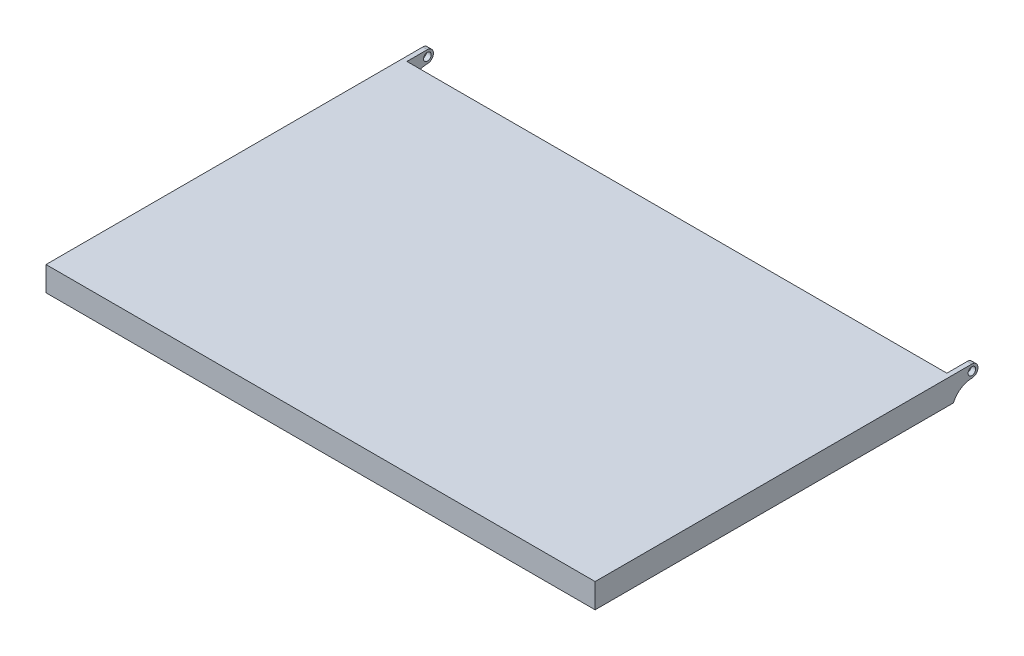
SolidWorks part; units mm, degrees
ref_plane "Alzado" through (0, 0, 0) normal (0, 0, 1) x (1, 0, 0)
ref_plane "Planta" through (0, 0, 0) normal (0, 1, 0) x (1, 0, 0)
ref_plane "Vista lateral" through (0, 0, 0) normal (1, 0, 0) x (0, 0, -1)
sketch "Croquis1" plane through (0, 0, 0) normal (0, 1, 0) x (1, 0, 0)
  line L0 (63.5, 63.5) -> (63.5, 390.652) construction
  line L1 (0, 0) -> (654.05, 0) construction
  line L2 (0, 0) -> (0, 454.152) construction
  line L3 (0, 454.152) -> (654.05, 454.152) construction
  line L4 (654.05, 0) -> (654.05, 454.152) construction
  line L5 (63.5, 390.652) -> (590.55, 390.652) construction
  line L6 (590.55, 63.5) -> (590.55, 390.652) construction
  line L7 (63.5, 63.5) -> (590.55, 63.5) construction
  line L8 (42.3333, 411.8187) -> (611.7167, 411.8187)
  line L9 (611.7167, 42.3333) -> (611.7167, 411.8187)
  line L10 (42.3333, 42.3333) -> (611.7167, 42.3333)
  line L11 (42.3333, 42.3333) -> (42.3333, 411.8187)
  dimension "D1" = 654.05
  dimension "D2" = 454.152
  dimension "D4" = 21.1667
  dimension "D5" = 42.3333
  dimension "D3" = 63.5
extrude "Saliente-Extruir1" add sketch "Croquis1" along normal blind 25.4
shell "Vaciado1" thickness 3.175
sketch "Croquis2" plane through (611.7167, 0, 0) normal (1, 0, 0) x (0, 0, -1)
  line L0 (411.8187, 25.4) -> (454.1487, 25.4) construction
  line L1 (454.1487, 25.4) -> (454.1487, 12.7) construction
  line L2 (454.1487, 12.7) -> (411.8187, 12.7) construction
  line L3 (411.8187, 25.4) -> (411.8187, 0) construction
  line L4 (432.9837, 25.4) -> (432.9837, 12.7) construction
  line L5 (411.8187, 0) -> (411.8187, 25.4)
  line L6 (411.8187, 25.4) -> (432.9837, 25.4)
  line L7 (439.3337, 0) -> (413.9337, 0) construction
  line L8 (439.3337, 19.05) -> (439.3337, 0) construction
  line L9 (411.8187, 0) -> (413.9337, 0)
  circle A0 centre (432.9837, 19.05) radius 3.9688
  arc A1 (432.9837, 12.7) -> (432.9837, 25.4) centre (432.9837, 19.05) ccw
  arc A3 (413.9337, 0) -> (432.9837, 12.7) centre (432.9837, -7.9375) cw
  dimension "D2" = 7.9375
  dimension "D4" = 2.115
  dimension "D1" = 42.33
  dimension "D3" = 25.4
extrude "Saliente-Extruir2" add sketch "Croquis2" against normal blind 4.7625
ref_plane "Plano1" through (327.025, 0, 0) normal (1, 0, 0) x (0, 0, -1)
mirror "Simetría1" about plane through (327.025, 0, 0) normal (1, 0, 0) of "Saliente-Extruir2"
